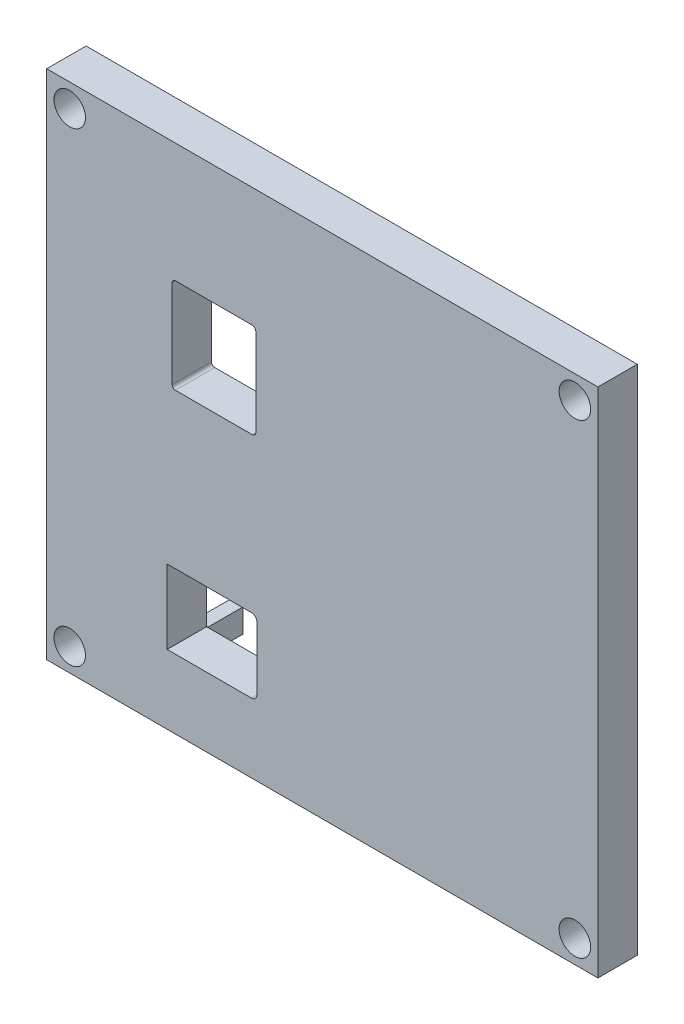
SolidWorks part; units mm, degrees
ref_plane "Ebene vorne" through (0, 0, 0) normal (0, 0, 1) x (1, 0, 0)
ref_plane "Ebene oben" through (0, 0, 0) normal (0, 1, 0) x (1, 0, 0)
ref_plane "Ebene rechts" through (0, 0, 0) normal (1, 0, 0) x (0, 0, -1)
sketch "Skizze1" plane through (0, 0, 0) normal (0, 0, 1) x (1, 0, 0)
  line L0 (70, 59.15) -> (70, 5.85)
  line L1 (25.99, 49.85) -> (26.09, 49.85)
  line L2 (25.99, 37.81) -> (26.09, 37.81)
  line L16 (70, 0) -> (70, 5.85)
  line L17 (70, 5.85) -> (13.85, 5.85)
  line L18 (13.85, 5.85) -> (13.85, 6.85)
  line L19 (13.85, 6.85) -> (10.85, 6.85)
  line L20 (10.85, 6.85) -> (10.85, 5.85)
  line L21 (10.85, 5.85) -> (5.85, 5.85)
  line L22 (5.85, 5.85) -> (5.85, 59.15)
  line L23 (5.85, 59.15) -> (10.85, 59.15)
  line L24 (10.85, 59.15) -> (10.85, 58.15)
  line L25 (10.85, 58.15) -> (13.85, 58.15)
  line L26 (13.85, 58.15) -> (13.85, 59.15)
  line L27 (13.85, 59.15) -> (70, 59.15)
  line L28 (70, 59.15) -> (70, 65)
  line L29 (70, 65) -> (0, 65)
  line L30 (0, 65) -> (0, 0)
  line L31 (0, 0) -> (70, 0)
  line L32 (70, 0) -> (70, 5.85)
  line L34 (13.85, 5.85) -> (13.85, 6.85)
  line L44 (70, 59.15) -> (70, 65)
  line L45 (70, 65) -> (0, 65)
  line L46 (0, 65) -> (0, 0)
  line L47 (0, 0) -> (70, 0)
  line L67 (26.7, 9.485) -> (26.7, 17.485)
  line L68 (15.3, 8.785) -> (26, 8.785)
  line L69 (15.3, 18.185) -> (15.3, 8.785)
  line L70 (26, 18.185) -> (15.3, 18.185)
  line L71 (26.7, 9.485) -> (26.7, 17.485)
  line L72 (15.3, 8.785) -> (26, 8.785)
  line L73 (15.3, 18.185) -> (15.3, 8.785)
  line L74 (26, 18.185) -> (15.3, 18.185)
  line L77 (25.99, 49.85) -> (16.34, 49.85) construction
  line L78 (26.55, 38.27) -> (26.55, 49.39) construction
  line L84 (16.34, 37.81) -> (25.99, 37.81) construction
  line L86 (15.93, 49.85) -> (15.93, 37.81) construction
  line L87 (15.93, 49.44) -> (15.93, 38.22)
  line L88 (16.34, 37.81) -> (25.99, 37.81)
  line L89 (26.55, 38.27) -> (26.55, 49.39)
  line L90 (25.99, 49.85) -> (16.34, 49.85)
  circle A0 centre (67.075, 62.075) radius 2 construction
  circle A1 centre (67.075, 62.075) radius 2
  circle A2 centre (2.925, 2.925) radius 2 construction
  circle A3 centre (2.925, 62.075) radius 2 construction
  circle A4 centre (67.075, 2.925) radius 2 construction
  circle A5 centre (2.925, 2.925) radius 2
  circle A6 centre (2.925, 62.075) radius 2
  circle A7 centre (67.075, 2.925) radius 2
  arc A8 (15.93, 38.22) -> (16.34, 37.81) centre (16.34, 38.22) ccw construction
  arc A9 (26.09, 37.81) -> (26.55, 38.27) centre (26.09, 38.27) ccw construction
  arc A10 (16.34, 49.85) -> (15.93, 49.44) centre (16.34, 49.44) ccw construction
  arc A11 (26.55, 49.39) -> (26.09, 49.85) centre (26.09, 49.39) ccw construction
  arc A12 (15.93, 38.22) -> (16.34, 37.81) centre (16.34, 38.22) ccw
  arc A13 (26.09, 37.81) -> (26.55, 38.27) centre (26.09, 38.27) ccw
  arc A14 (16.34, 49.85) -> (15.93, 49.44) centre (16.34, 49.44) ccw
  arc A15 (26.55, 49.39) -> (26.09, 49.85) centre (26.09, 49.39) ccw
  arc A23 (26.7, 17.485) -> (26, 18.185) centre (26, 17.485) ccw
  arc A24 (26, 8.785) -> (26.7, 9.485) centre (26, 9.485) ccw
  arc A25 (26.7, 17.485) -> (26, 18.185) centre (26, 17.485) ccw
  arc A26 (26, 8.785) -> (26.7, 9.485) centre (26, 9.485) ccw
  dimension "D1" = 0
  dimension "D2" = 0.2
extrude "Aufsatz-Linear austragen1" add sketch "Skizze1" along normal blind 5
sketch "Skizze2" plane through (0, 5.85, 0) normal (0, 1, 0) x (1, 0, 0)
  line L0 (0, 0) -> (70, 0) construction
  line L1 (15.5, 4.42) -> (13.85, 4.42)
  line L2 (15.5, 4.42) -> (15.5, 0)
  line L3 (15.5, 0) -> (13.85, 0)
  line L4 (13.85, 4.42) -> (13.85, 0)
  line L5 (13.85, 73) -> (13.85, 0) construction
extrude "Aufsatz-Linear austragen2" add sketch "Skizze2" along normal blind 3
sketch "Skizze3" plane through (0, 59.15, 0) normal (0, -1, 0) x (1, 0, 0)
  line L1 (13.85, -4.42) -> (15.93, -4.42)
  line L2 (13.85, -4.42) -> (13.85, 0)
  line L3 (13.85, 0) -> (15.93, 0)
  line L4 (15.93, -4.42) -> (15.93, 0)
extrude "Aufsatz-Linear austragen3" add sketch "Skizze3" along normal blind 3
